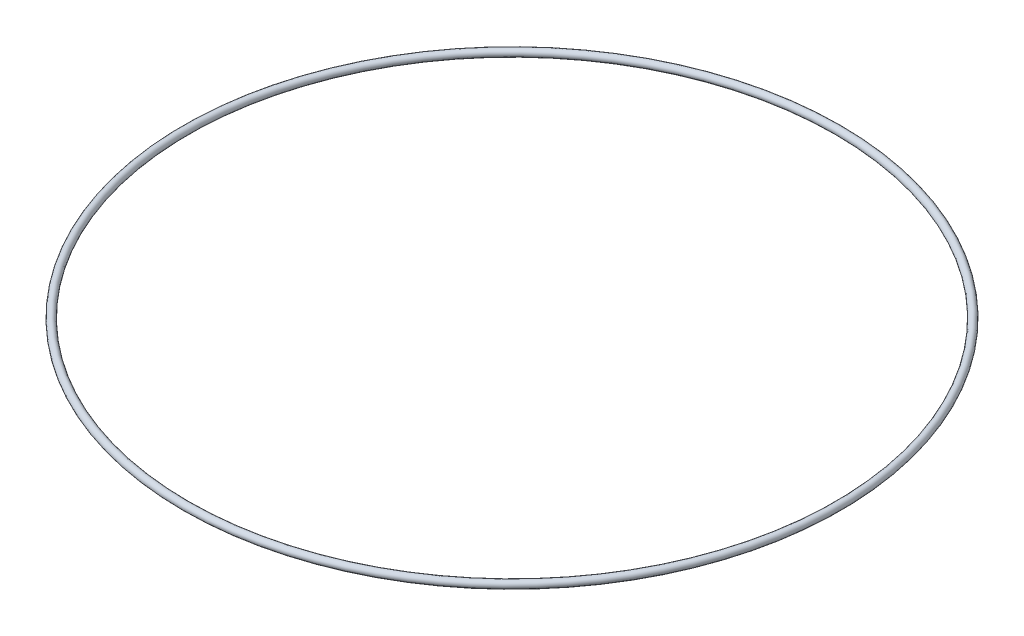
SolidWorks part; units mm, degrees
ref_plane "Front Plane" through (0, 0, 0) normal (0, 0, 1) x (1, 0, 0)
ref_plane "Top Plane" through (0, 0, 0) normal (0, 1, 0) x (1, 0, 0)
ref_plane "Right Plane" through (0, 0, 0) normal (1, 0, 0) x (0, 0, -1)
sketch "Sketch2" plane through (0, 0, 0) normal (1, 0, 0) x (0, 0, -1)
  circle A0 centre (220, 0) radius 2.5
  dimension "D1" = 5
  dimension "D2" = 220
ref_axis "Axis1" through (0, 0, 0) along (0, 1, 0)
revolve "Revolve1" add sketch "Sketch2" angle 360 about axis through (0, 0, 0) along (0, 1, 0)
